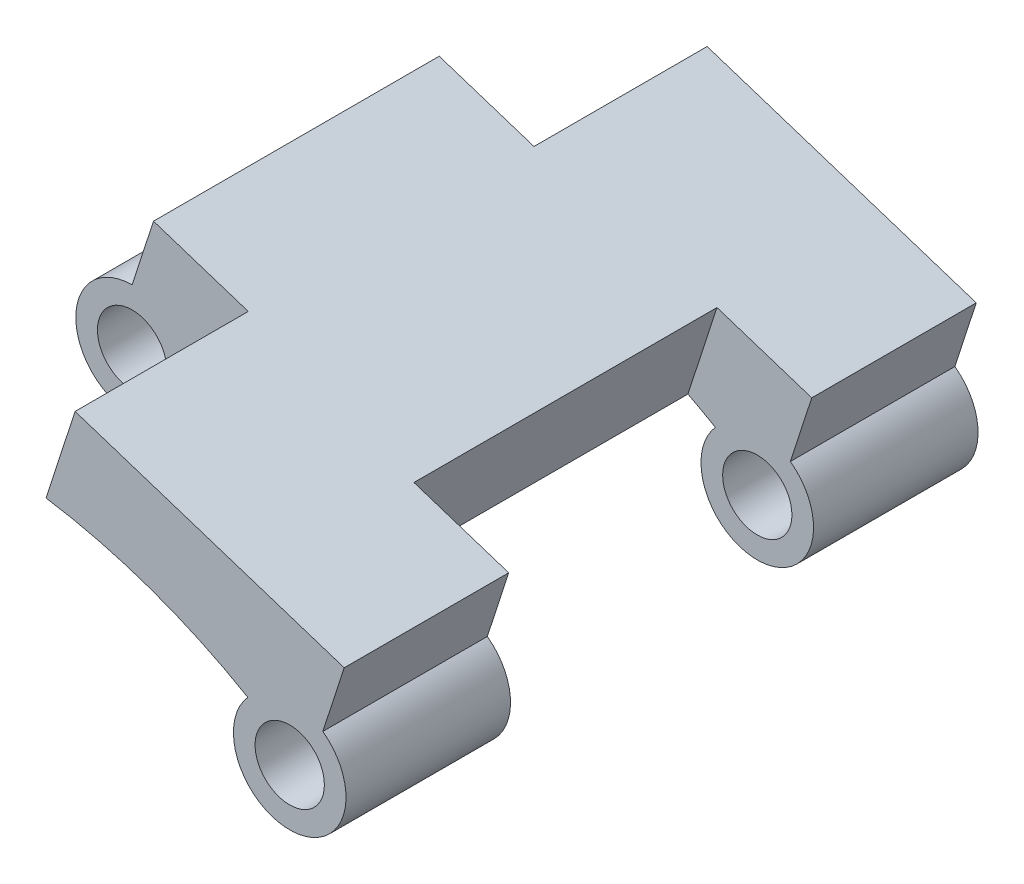
SolidWorks part; units mm, degrees
ref_plane "Alzado" through (0, 0, 0) normal (0, 0, 1) x (1, 0, 0)
ref_plane "Planta" through (0, 0, 0) normal (0, 1, 0) x (1, 0, 0)
ref_plane "Vista lateral" through (0, 0, 0) normal (1, 0, 0) x (0, 0, -1)
sketch "Croquis1" plane through (0, 0, 0) normal (0, 0, 1) x (1, 0, 0)
  line L0 (6.5438, 33.5384) -> (4.5438, 33.5384)
  line L1 (3.0489, 33.5384) -> (3.0489, 33.3499)
  line L2 (6.5438, 33.5384) -> (8.5438, 33.5384)
  line L3 (10.0419, 33.5384) -> (10.0351, 33.2913)
  line L4 (6.5438, 33.5384) -> (8.4459, 32.9204)
  line L5 (24.4712, 25.7134) -> (26.8224, 28.9495)
  line L6 (6.5438, 31.5384) -> (6.5438, 35.5384)
  line L8 (28.7932, 33.765) -> (7.7799, 40.5926)
  line L9 (27.5571, 29.9608) -> (28.7932, 33.765)
  line L10 (6.5438, 36.7884) -> (7.7799, 40.5926)
  line L11 (23.7447, 27.9495) -> (25.6468, 27.3314)
  line L12 (9.7938, 33.5384) -> (10.0419, 33.5384)
  line L13 (3.2938, 33.5384) -> (3.0489, 33.5384)
  arc A0 (6.5438, 36.7884) -> (9.7768, 33.8707) centre (6.5438, 33.5384) ccw
  circle A1 centre (6.5438, 33.5384) radius 2
  arc A2 (23.2266, 29.5006) -> (27.5571, 29.9608) centre (25.6468, 27.3314) ccw
  circle A3 centre (25.6468, 27.3314) radius 2
  arc A5 (27.4811, 26.5343) -> (24.3218, 28.8296) centre (6.5438, 1.0384) ccw
  arc A6 (23.2266, 29.5006) -> (9.7768, 33.8707) centre (6.5438, 1.0384) ccw
  arc A7 (8.4963, 33.9716) -> (4.5913, 33.9716) centre (6.5438, 1.0384) ccw
  dimension "D1" = 6.5
  dimension "D2" = 4
  dimension "D3" = 6.5
  dimension "D4" = 4
  dimension "D5" = 4
extrude "Saliente-Extruir1" add sketch "Croquis1" along normal blind 6.5 and the other way blind 30 contours A3 A5 L5 | L11 A3 L5 | L5 A5 A3 L11 | A5 L5 A3 | A5 A3 L5 | A1 | A0 A6 A2 L9 L8 L10
sketch "Croquis2" plane through (12.6728, 39.0028, 0) normal (0.309, 0.9511, 0) x (0.9511, -0.309, 0)
  line L0 (-7.3904, 11.75) -> (19.1957, 11.75) construction
  line L1 (-7.3904, 30) -> (-7.3904, -6.5) construction
  line L2 (19.1957, -6.5) -> (19.1957, 30) construction
  line L3 (-0.8904, 30) -> (-7.3904, 30) construction
  line L4 (-7.3904, 30) -> (0.6096, 30)
  line L5 (-7.3904, 30) -> (-7.3904, 20)
  line L6 (-7.3904, 20) -> (0.6096, 20)
  line L7 (0.6096, 30) -> (0.6096, 20)
  line L9 (-7.3904, -6.5) -> (0.6096, -6.5)
  line L10 (-7.3904, -6.5) -> (-7.3904, 3.5)
  line L11 (-7.3904, 3.5) -> (0.6096, 3.5)
  line L12 (0.6096, -6.5) -> (0.6096, 3.5)
  line L13 (19.1957, 20.5) -> (11.1957, 20.5)
  line L14 (19.1957, 20.5) -> (19.1957, 3)
  line L15 (19.1957, 3) -> (11.1957, 3)
  line L16 (11.1957, 20.5) -> (11.1957, 3)
  point P20 (11.1957, 11.75)
  dimension "D1" = 10
  dimension "D2" = 10
  dimension "D3" = 8
  dimension "D4" = 8
  dimension "D5" = 8
  dimension "D6" = 17.5
extrude "Cortar-Extruir2" cut sketch "Croquis2" against normal blind 20
ref_plane "Plano1" through (0, 0, -11.75) normal (0, 0, 1) x (1, 0, 0)
